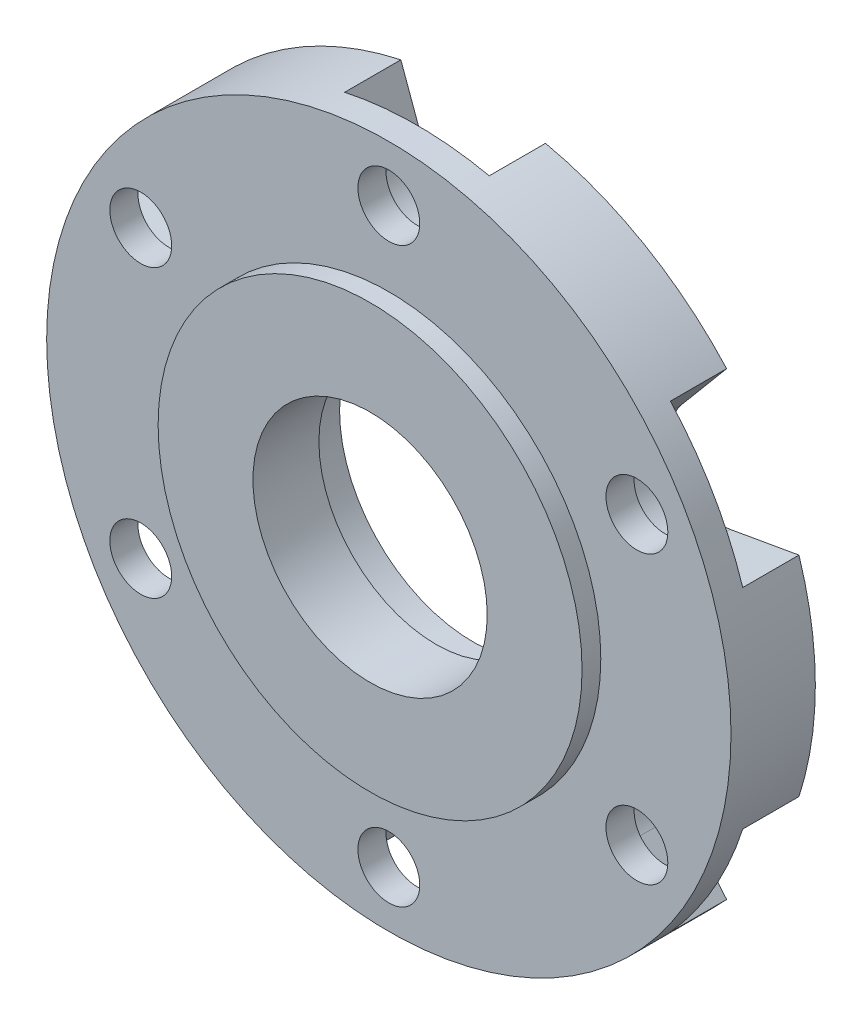
SolidWorks part; units mm, degrees
material "6061-T6 (SS)"
ref_plane "Front Plane" through (0, 0, 0) normal (0, 0, 1) x (1, 0, 0)
ref_plane "Top Plane" through (0, 0, 0) normal (0, 1, 0) x (1, 0, 0)
ref_plane "Right Plane" through (0, 0, 0) normal (1, 0, 0) x (0, 0, -1)
sketch "Sketch Spindle Skeleton" plane through (0, 0, 0) normal (1, 0, 0) x (0, 0, -1)
  line L0 (-95.847, -9.525) -> (-140.95, -9.525)
  line L5 (-1000, 0) -> (49000, 0)
  line L6 (0, -9.525) -> (0, 9.525)
  line L13 (0, 9.525) -> (-45.847, 9.525)
  line L26 (-45.847, 9.525) -> (-45.847, 14)
  line L27 (-45.847, 14) -> (-95.847, 14)
  line L32 (-95.847, 14) -> (-95.847, 9.525)
  line L34 (-160, 7) -> (-160, -7)
  line L36 (-95.847, -9.525) -> (-95.847, -14)
  line L37 (-95.847, -14) -> (-45.847, -14)
  line L38 (-45.847, -14) -> (-45.847, -9.525)
  line L39 (0, -9.525) -> (-45.847, -9.525)
  line L40 (-26.321, 36.5125) -> (-17.321, 36.5125)
  line L41 (-111.341, 22.6187) -> (-95.847, 22.6187)
  line L42 (-111.341, 22.6187) -> (-111.341, -22.6187)
  line L43 (-111.341, -22.6187) -> (-95.847, -22.6187)
  line L44 (-95.847, 22.6187) -> (-95.847, -22.6187)
  line L45 (-111.341, 22.6187) -> (-95.847, -22.6187) construction
  line L46 (-111.341, -22.6187) -> (-95.847, 22.6187) construction
  line L47 (-30.353, 22.6187) -> (-45.847, 22.6187)
  line L48 (-30.353, 22.6187) -> (-30.353, -22.6187)
  line L49 (-30.353, -22.6187) -> (-45.847, -22.6187)
  line L50 (-45.847, 22.6187) -> (-45.847, -22.6187)
  line L51 (-30.353, 22.6187) -> (-45.847, -22.6187) construction
  line L52 (-30.353, -22.6187) -> (-45.847, 22.6187) construction
  line L59 (-17.321, 36.5125) -> (-17.321, -36.5125)
  line L60 (-17.321, -36.5125) -> (-26.321, -36.5125)
  line L61 (-26.321, -22.6187) -> (-28.321, -22.6187)
  line L62 (-28.321, -22.6187) -> (-28.321, -12.5)
  line L63 (-28.321, -12.5) -> (-26.321, -12.5)
  line L64 (-26.321, -12.5) -> (-26.321, 12.5)
  line L65 (-26.321, 12.5) -> (-28.321, 12.5)
  line L66 (-28.321, 12.5) -> (-28.321, 22.6187)
  line L67 (-28.321, 22.6187) -> (-26.321, 22.6187)
  line L68 (-26.321, 22.6187) -> (-26.321, 36.5125)
  line L69 (-26.321, -22.6187) -> (-26.321, -36.5125)
  line L71 (-119.469, 36.5125) -> (-26.321, 36.5125)
  line L72 (-119.469, 36.5125) -> (-119.469, -36.5125)
  line L73 (-119.469, -36.5125) -> (-26.321, -36.5125)
  line L74 (-26.321, 36.5125) -> (-26.321, -36.5125)
  line L75 (-119.469, 36.5125) -> (-26.321, -36.5125) construction
  line L76 (-119.469, -36.5125) -> (-26.321, 36.5125) construction
  line L77 (-140.95, -9.525) -> (-140.95, -7)
  line L78 (-140.95, -7) -> (-160, -7)
  line L79 (-95.847, 9.525) -> (-140.95, 9.525)
  line L80 (-140.95, 7) -> (-160, 7)
  line L81 (-140.95, 9.525) -> (-140.95, 7)
  line L82 (-118.3985, 9.525) -> (-118.3985, -9.525) construction
  line L83 (-22.9235, 9.525) -> (-22.9235, -9.525) construction
  line L96 (-119.469, 36.5125) -> (-134.709, 36.5125)
  line L98 (-119.469, -36.5125) -> (-134.709, -36.5125)
  line L99 (-134.709, 36.5125) -> (-134.709, -36.5125)
  line L110 (-119.469, 36.5125) -> (-119.469, -36.5125)
  point P3 (0, 0)
  point P18 (-103.594, 0)
  point P24 (-38.1, 0)
  point P29 (-72.895, 0)
  point P48 (-17.321, 30.5656)
  point P70 (-134.709, 31.75)
revolve "Main Revolve" add sketch "Sketch Spindle Skeleton" angle 360 about L5
sketch "Sketch Center Cut" plane through (0, 0, 26.321) normal (0, 0, 1) x (1, 0, 0)
  circle A3 centre (0, 0) radius 12.5
  dimension "D1" = 25
extrude "Cut Center" cut sketch "Sketch Center Cut" against normal through all both and the other way through all
hole_wizard "CBORE for M6 SHCS1" positions "Hole wizard sketch 1" profile "Hole wizard sketch 2" counterbore size "M6" standard "ANSI Metric" end condition through all
sketch "Hole wizard sketch 1" plane through (0, 0, 17.321) normal (0, 0, -1) x (-1, 0, 0)
  point P0 (0, 30.5656)
sketch "Hole wizard sketch 2" plane through (0, 30.5656, 17.321) normal (1, 0, 0) x (0, 1, 0)
  line L0 (0, 0) -> (0, 11)
  line L1 (0, 11) -> (3.3, 11)
  line L3 (3.3, 11) -> (3.3, 6)
  line L4 (3.3, 6) -> (5.5, 6)
  line L5 (5.5, 6) -> (5.5, 0)
  line L7 (5.5, 0) -> (0, 0)
  line L11 (0, -6.35) -> (0, 107.95) construction
  dimension "Thru Hole Dia." = 6.6
  dimension "Thru Hole Depth" = 11
  dimension "C'Bore Dia." = 11
  dimension "C'Bore Depth" = 6
pattern_circular "CirPattern1" count 6 over 360 about axis through (0, 0, 0) along (0, 0, 1) of "CBORE for M6 SHCS1"
sketch "Sketch1" plane through (0, 0, 17.321) normal (0, 0, -1) x (-1, 0, 0)
  circle A0 centre (0, 0) radius 14.2558
  dimension "D1" = 28.5115
extrude "Cut-Extrude1" cut sketch "Sketch1" against normal blind 3.9624
sketch "Sketch2" plane through (0, 0, 17.321) normal (0, 0, -1) x (-1, 0, 0)
  line L0 (-5.1683, 28.6845) -> (-7.7172, 35.6876)
  line L1 (0, 30.5656) -> (0, 37.65) construction
  line L2 (5.1683, 28.6845) -> (7.7172, 35.6876)
  circle A0 centre (0, 30.5656) radius 5.5 construction
  circle A1 centre (0, 0) radius 36.5125 construction
  arc A2 (-5.1683, 28.6845) -> (5.1683, 28.6845) centre (0, 30.5656) ccw
  point P37 (0.065, 0.0375)
  circle M8 centre (0, 30.5656) radius 5.5
  circle M9 centre (0, 0) radius 36.5125
  dimension "D1" = 20
extrude "Cut-Extrude2" cut sketch "Sketch2" against normal up to surface (6 mm away) contours L1 L2 M8 M9 | L1 L0 M8 M9 up to face at (23.1706, -15.2828, 23.321)
pattern_circular "CirPattern2" count 6 over 360 about axis through (0, 0, 0) along (0, 0, 1) of "Cut-Extrude2"
